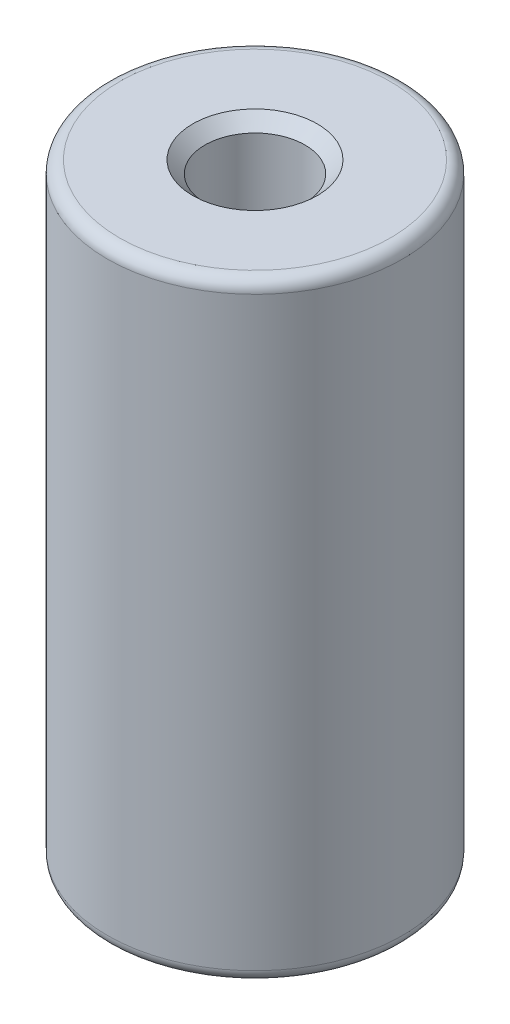
SolidWorks part; units mm, degrees
ref_plane "Front Plane" through (0, 0, 0) normal (0, 0, 1) x (1, 0, 0)
ref_plane "Top Plane" through (0, 0, 0) normal (0, 1, 0) x (1, 0, 0)
ref_plane "Right Plane" through (0, 0, 0) normal (1, 0, 0) x (0, 0, -1)
sketch "Sketch1" plane through (0, 0, 0) normal (0, 1, 0) x (1, 0, 0)
  circle A0 centre (0, 0) radius 2.05
  circle A1 centre (0, 0) radius 6.05
  dimension "D1" = 4.1
  dimension "D2" = 4
extrude "Boss-Extrude1" add sketch "Sketch1" along normal blind 25
chamfer "Chamfer1" distance 0.5 angle 45 2 edges at (0, 0, 2.05) (0, 25, 2.05)
fillet "Fillet1" radius 0.5 2 edges at (0, 0, 6.05) (0, 25, 6.05)
